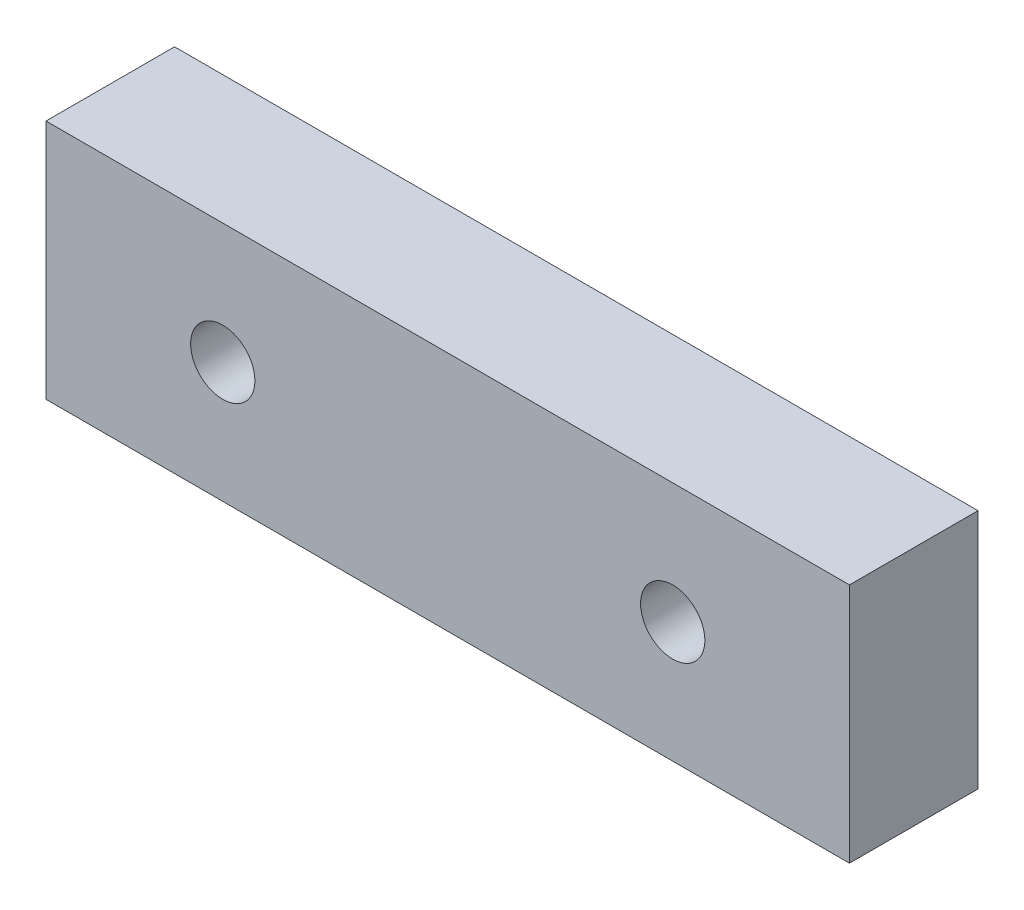
SolidWorks part; units mm, degrees
material "POM 乙缩醛共聚物"
ref_plane "前视基准面" through (0, 0, 0) normal (0, 0, 1) x (1, 0, 0)
ref_plane "上视基准面" through (0, 0, 0) normal (0, 1, 0) x (1, 0, 0)
ref_plane "右视基准面" through (0, 0, 0) normal (1, 0, 0) x (0, 0, -1)
sketch "草图1" plane through (0, 0, 0) normal (0, 0, 1) x (1, 0, 0)
  line L1 (-25, 7.5) -> (25, 7.5)
  line L2 (-25, 7.5) -> (-25, -7.5)
  line L3 (-25, -7.5) -> (25, -7.5)
  line L4 (25, 7.5) -> (25, -7.5)
  line L5 (-25, 7.5) -> (25, -7.5) construction
  line L6 (-25, -7.5) -> (25, 7.5) construction
  point P0 (0, 0)
  dimension "D1" = 15
  dimension "D2" = 50
extrude "凸台-拉伸1" add sketch "草图1" along normal blind 8
sketch "草图2" plane through (0, 0, 8) normal (0, 0, 1) x (1, 0, 0)
  line L0 (-25, 0) -> (25, 0) construction
  line L1 (-25, 7.5) -> (-25, -7.5) construction
  line L2 (25, -7.5) -> (25, 7.5) construction
  line L3 (0, 7.5) -> (0, -7.5) construction
  line L4 (25, 7.5) -> (-25, 7.5) construction
  line L5 (-25, -7.5) -> (25, -7.5) construction
  circle A0 centre (-14, 0) radius 2
  circle A1 centre (14, 0) radius 2
  dimension "D1" = 4
  dimension "D2" = 14
extrude "切除-拉伸1" cut sketch "草图2" against normal through all
